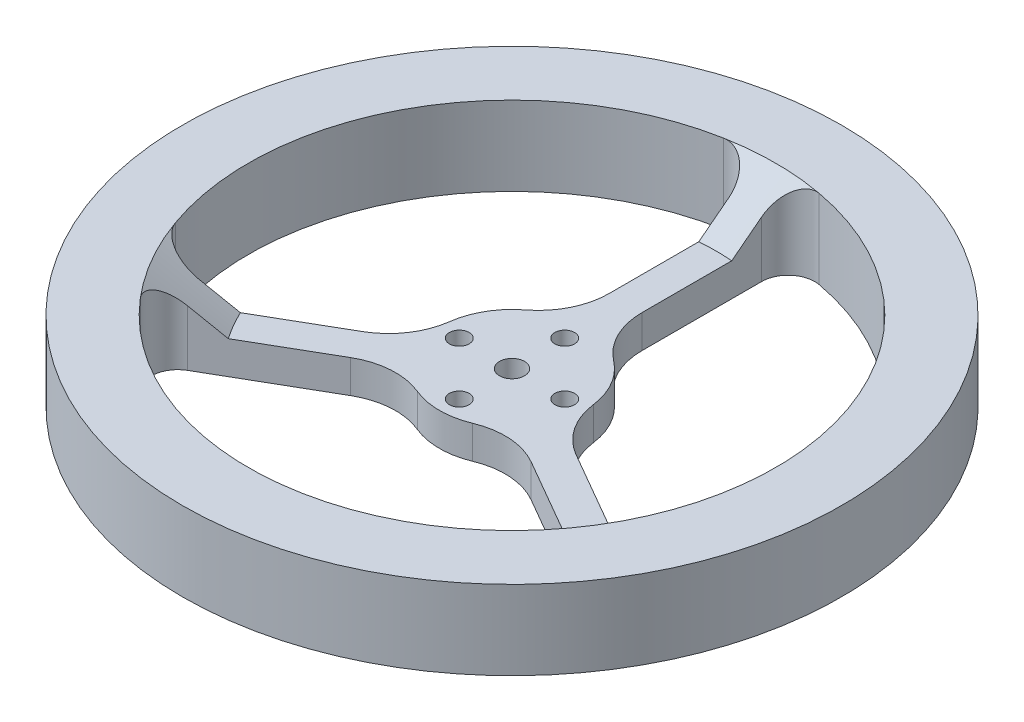
SolidWorks part; units mm, degrees
ref_plane "Front Plane" through (0, 0, 0) normal (0, 0, 1) x (1, 0, 0)
ref_plane "Top Plane" through (0, 0, 0) normal (0, 1, 0) x (1, 0, 0)
ref_plane "Right Plane" through (0, 0, 0) normal (1, 0, 0) x (0, 0, -1)
sketch "Sketch1" plane through (0, 0, 0) normal (0, 1, 0) x (1, 0, 0)
  circle A0 centre (0, 0) radius 50
  circle A1 centre (0, 0) radius 1.9
  dimension "D1" = 100
  dimension "D2" = 3.8
extrude "Boss-Extrude1" add sketch "Sketch1" along normal blind 12
sketch "Sketch3" plane through (0, 12, 0) normal (0, 1, 0) x (1, 0, 0)
  line L0 (-2.5, 10.7121) -> (-2.5, 39.9218)
  line L25 (2.5, 10.7121) -> (2.5, 39.9218)
  line L26 (0, 0) -> (0, 55.5592) construction
  line L27 (-2.5, 39.9218) -> (2.5, 39.9218) construction
  line L28 (10.527, -3.191) -> (35.8233, -17.7958)
  line L29 (8.027, -7.5211) -> (33.3233, -22.126)
  line L30 (35.8233, -17.7958) -> (33.3233, -22.126) construction
  line L31 (-8.027, -7.5211) -> (-33.3233, -22.126)
  line L32 (-10.527, -3.191) -> (-35.8233, -17.7958)
  line L33 (-33.3233, -22.126) -> (-35.8233, -17.7958) construction
  circle A2 centre (0, 0) radius 11
  circle A3 centre (0, 0) radius 40
  arc A6 (-2.5, 35.3631) -> (-7.2717, 39.3335) centre (-6.5377, 35.3631) ccw
  circle A13 centre (0, 0) radius 50 construction
  arc A14 (2.5, 17.2396) -> (6.6977, 8.7259) centre (13.2325, 17.2396) ccw
  arc A15 (-6.6977, 8.7259) -> (-2.5, 17.2396) centre (-13.2325, 17.2396) ccw
  arc A16 (7.2717, 39.3335) -> (2.5, 35.3631) centre (6.5377, 35.3631) ccw
  circle A17 centre (0, 0) radius 11
  arc A18 (31.8753, -15.5165) -> (37.6996, -13.3693) centre (33.8942, -12.0197) ccw
  arc A19 (13.6799, -10.7849) -> (4.208, -10.1633) centre (8.3136, -20.0795) ccw
  arc A20 (10.9057, 1.4374) -> (16.1799, -6.4547) centre (21.5462, 2.8399) ccw
  arc A21 (30.4279, -25.9642) -> (29.3753, -19.8466) centre (27.3565, -23.3433) ccw
  circle A22 centre (0, 0) radius 11
  arc A23 (-29.3753, -19.8466) -> (-30.4279, -25.9642) centre (-27.3565, -23.3433) ccw
  arc A24 (-16.1799, -6.4547) -> (-10.9057, 1.4374) centre (-21.5462, 2.8399) ccw
  arc A25 (-4.208, -10.1633) -> (-13.6799, -10.7849) centre (-8.3136, -20.0795) ccw
  arc A26 (-37.6996, -13.3693) -> (-31.8753, -15.5165) centre (-33.8942, -12.0197) ccw
  point P10 (0, 39.9218)
  point P19 (13.6799, 17.2396)
  point P60 (0, 0)
  dimension "D1" = 22
  dimension "D2" = 10
  dimension "D3" = 3
  dimension "5" = 5
extrude "Cut-Extrude5" cut sketch "Sketch3" against normal up to surface (12 mm away) contours A22 A25 L31 A23 A3 A21 L29 A19 | A3 A26 L32 A24 A2 A15 L0 A6 | A17 A20 L28 A18 A3 A16 L25 A14
sketch "Sketch7" plane through (0, 0, 0) normal (0, 0, 1) x (1, 0, 0)
  line L0 (40, 12) -> (30.939, 5)
  line L1 (50, 12) -> (-50, 12) construction
  line L2 (30.939, 5) -> (0, 5)
  line L3 (0, 5) -> (0, 12)
  line L4 (30.4279, 12) -> (-30.4279, 12) construction
  line L5 (0, 12) -> (40, 12)
  point P4 (30.939, 5)
  dimension "D1" = 10
  dimension "D2" = 5
revolve "Cut-Revolve1" cut sketch "Sketch7" angle 360 about L3
sketch "Sketch8" plane through (0, 0, 0) normal (0, 1, 0) x (1, 0, 0)
  circle A0 centre (0, 0) radius 8 construction
  circle A1 centre (0, 8) radius 1.5
  circle A2 centre (8, 0) radius 1.5
  circle A3 centre (0, -8) radius 1.5
  circle A4 centre (-8, 0) radius 1.5
  point P14 (0, 0)
  dimension "D1" = 16
  dimension "D2" = 3
  dimension "D3" = 4
extrude "Cut-Extrude8" cut sketch "Sketch8" along normal blind 10
